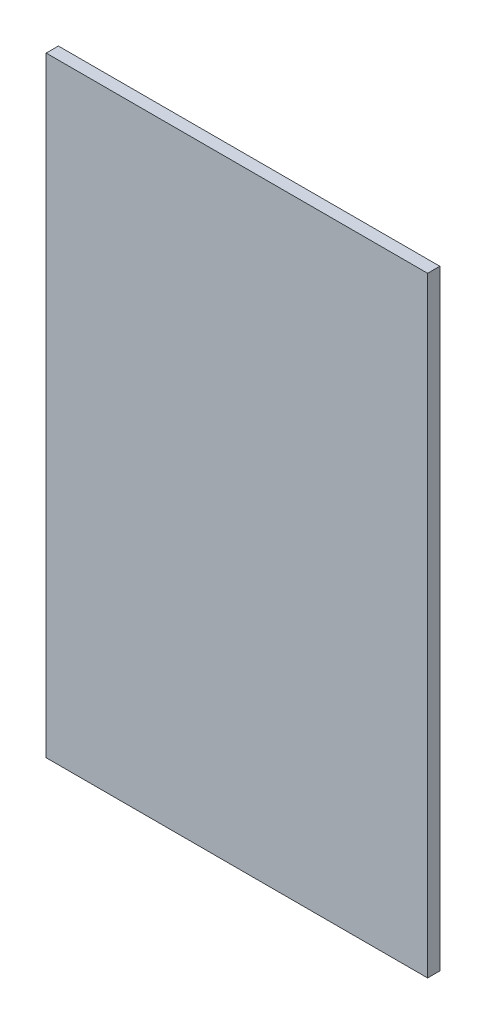
SolidWorks part; units mm, degrees
ref_plane "Front Plane" through (0, 0, 0) normal (0, 0, 1) x (1, 0, 0)
ref_plane "Top Plane" through (0, 0, 0) normal (0, 1, 0) x (1, 0, 0)
ref_plane "Right Plane" through (0, 0, 0) normal (1, 0, 0) x (0, 0, -1)
sketch "Sketch1" plane through (0, 0, 0) normal (0, 0, 1) x (1, 0, 0)
  line L1 (-90.767, -2.4807) -> (-65.767, -2.4807)
  line L2 (-90.767, -2.4807) -> (-90.767, -42.4807)
  line L3 (-90.767, -42.4807) -> (-65.767, -42.4807)
  line L4 (-65.767, -2.4807) -> (-65.767, -42.4807)
  dimension "D1" = 40
  dimension "D2" = 25
extrude "Boss-Extrude1" add sketch "Sketch1" along normal blind 0.8
